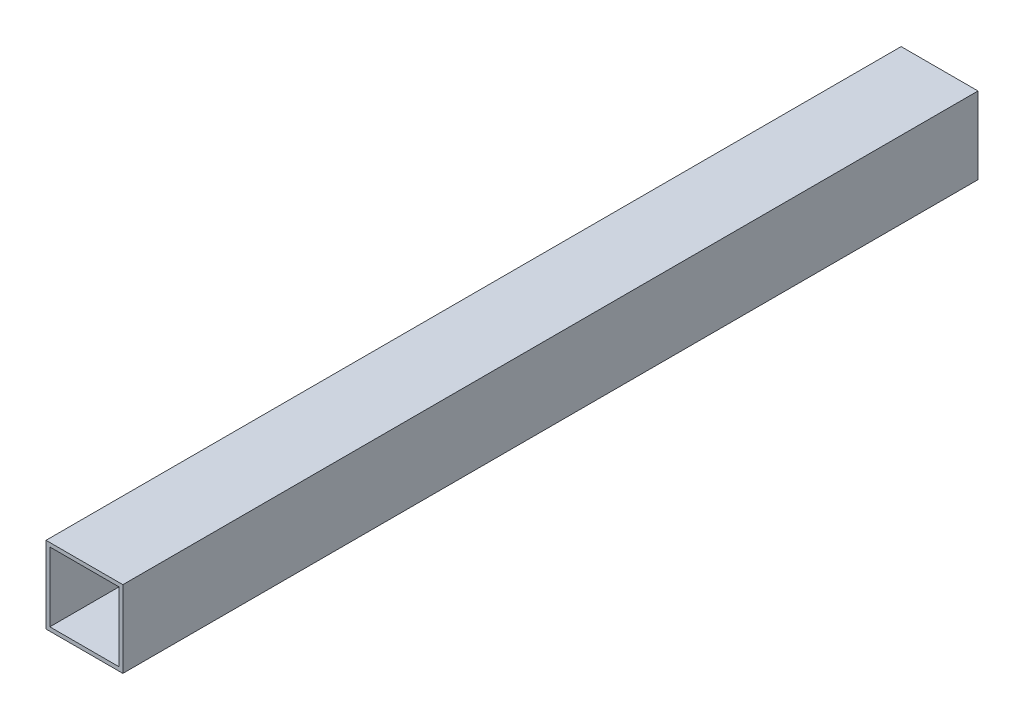
SolidWorks part; units mm, degrees
ref_plane "Alzado" through (0, 0, 0) normal (0, 0, 1) x (1, 0, 0)
ref_plane "Planta" through (0, 0, 0) normal (0, 1, 0) x (1, 0, 0)
ref_plane "Vista lateral" through (0, 0, 0) normal (1, 0, 0) x (0, 0, -1)
sketch "Croquis1" plane through (0, 0, 0) normal (0, 0, 1) x (1, 0, 0)
  line L1 (20, -20) -> (-20, -20)
  line L2 (20, -20) -> (20, 20)
  line L3 (20, 20) -> (-20, 20)
  line L4 (-20, -20) -> (-20, 20)
  line L5 (20, -20) -> (-20, 20) construction
  line L6 (20, 20) -> (-20, -20) construction
  point P0 (0, 0)
  dimension "D1" = 40
  dimension "D2" = 40
extrude "Extruir-Lámina1" add sketch "Croquis1" along normal blind 445 thin
